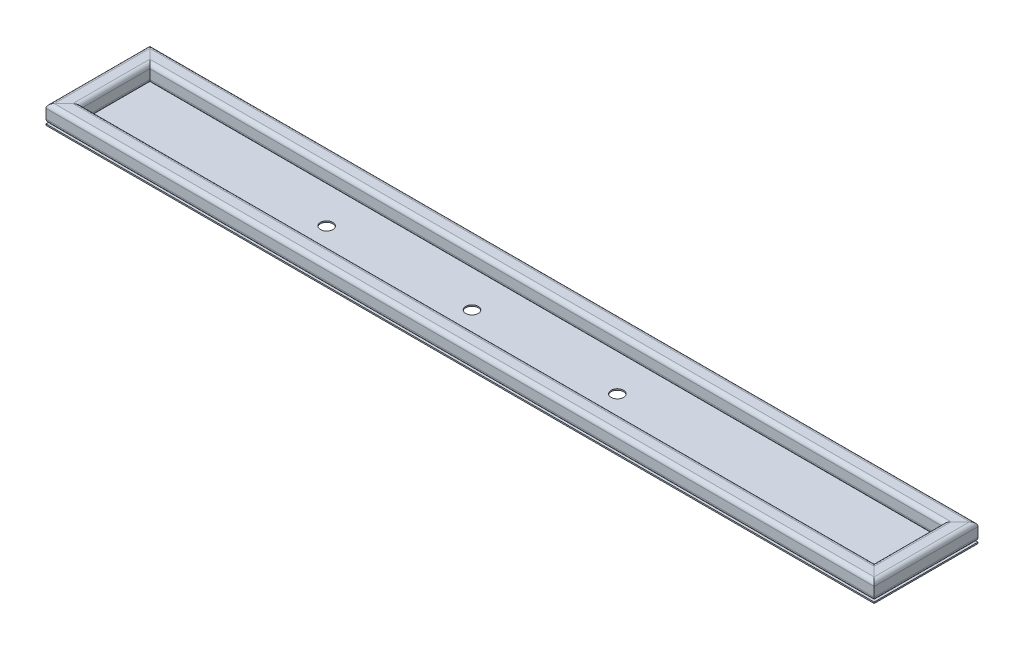
SolidWorks part; units mm, degrees
ref_plane "Alzado" through (0, 0, 0) normal (0, 0, 1) x (1, 0, 0)
ref_plane "Planta" through (0, 0, 0) normal (0, 1, 0) x (1, 0, 0)
ref_plane "Vista lateral" through (0, 0, 0) normal (1, 0, 0) x (0, 0, -1)
sketch "Croquis1" plane through (0, 0, 0) normal (0, 1, 0) x (1, 0, 0)
  line L1 (-598.2, 75) -> (598.2, 75)
  line L2 (-598.2, 75) -> (-598.2, -75)
  line L3 (-598.2, -75) -> (598.2, -75)
  line L4 (598.2, 75) -> (598.2, -75)
  line L5 (-598.2, 75) -> (598.2, -75) construction
  line L6 (-598.2, -75) -> (598.2, 75) construction
  point P0 (0, 0)
  dimension "D1" = 150
  dimension "D2" = 1196.4
other "Tubo cuadrado 2 X 2 X 0.25(1)"
ref_plane "Plano1" through (-585.5, 12.7, -75) normal (0, 0, 1) x (1, 0, 0)
sketch "Sketch1" plane through (-585.5, 12.7, -75) normal (0, 0, 1) x (1, 0, 0)
  line L0 (-6.7, -9.7) -> (6.7, -9.7)
  line L1 (-9.7, -6.7) -> (-9.7, 6.7)
  line L2 (6.7, 9.7) -> (-6.7, 9.7)
  line L3 (9.7, 6.7) -> (9.7, -6.7)
  line L4 (-6.7, -12.7) -> (6.7, -12.7)
  line L5 (-12.7, -6.7) -> (-12.7, 6.7)
  line L6 (6.7, 12.7) -> (-6.7, 12.7)
  line L7 (12.7, 6.7) -> (12.7, -6.7)
  line L8 (0, 0) -> (9.7, 0) construction
  line L9 (0, 0) -> (0, 9.7) construction
  arc A0 (12.7, 6.7) -> (6.7, 12.7) centre (6.7, 6.7) ccw
  arc A1 (6.7, -12.7) -> (12.7, -6.7) centre (6.7, -6.7) ccw
  arc A2 (-12.7, -6.7) -> (-6.7, -12.7) centre (-6.7, -6.7) ccw
  arc A3 (-6.7, 12.7) -> (-12.7, 6.7) centre (-6.7, 6.7) ccw
  arc A4 (-6.7, 9.7) -> (-9.7, 6.7) centre (-6.7, 6.7) ccw
  arc A5 (9.7, 6.7) -> (6.7, 9.7) centre (6.7, 6.7) ccw
  arc A6 (6.7, -9.7) -> (9.7, -6.7) centre (6.7, -6.7) ccw
  arc A7 (-9.7, -6.7) -> (-6.7, -9.7) centre (-6.7, -6.7) ccw
  point P3 (0, 12.7)
  point P4 (12.7, 0)
  point P5 (0, -12.7)
  point P6 (-12.7, 0)
  point P7 (-12.7, 12.7)
  point P8 (-12.7, -12.7)
  point P33 (0, 0)
  point P35 (12.7, -12.7)
  point P36 (12.7, 12.7)
  point P37 (0, 0)
  dimension "D1" = 6
  dimension "Thickness" = 3
  dimension "V_leg" = 25.4
sketch "Croquis3" plane through (0, 0, 0) normal (0, -1, 0) x (1, 0, 0)
  line L1 (598.2, 75) -> (-598.2, 75)
  line L2 (598.2, 75) -> (598.2, -75)
  line L3 (598.2, -75) -> (-598.2, -75)
  line L4 (-598.2, 75) -> (-598.2, -75)
  line L5 (598.2, 75) -> (-598.2, -75) construction
  line L6 (598.2, -75) -> (-598.2, 75) construction
  point P0 (0, 0)
extrude "Saliente-Extruir1" add sketch "Croquis3" along normal blind 1.9 separate body
ref_plane "Plano2" through (0, 0, 0) normal (0, 0, 1) x (1, 0, 0)
sketch "Croquis4" plane through (0, 0, 0) normal (0, 1, 0) x (1, 0, 0)
  circle A0 centre (-268.2099, 0) radius 7.9375
  circle A3 centre (-58.2099, 0) radius 7.9375
  circle A6 centre (151.7851, 0) radius 7.9375
sketch "Croquis6" plane through (0, -1.9, 0) normal (0, -1, 0) x (1, 0, 0)
  line L0 (-598.2, 75) -> (-598.2, -75) construction
  line L1 (-598.2, -75) -> (-598.2, 0) construction
  line L2 (-598.2, 0) -> (-267.8, 0) construction
  line L3 (7.37, 0) -> (-7.37, 0) construction
  line L4 (-267.8, 0) -> (-57.8, 0) construction
  line L5 (-57.8, 0) -> (152.2, 0) construction
  line L6 (598.2, -75) -> (598.2, 75) construction
  circle A0 centre (-267.8, 0) radius 9
  circle A1 centre (-57.8, 0) radius 9
  circle A2 centre (152.2, 0) radius 9
  dimension "D4" = 18
  dimension "D5" = 18
  dimension "D6" = 18
  dimension "D1" = 446
  dimension "D2" = 210
  dimension "D3" = 210
extrude "Cortar-Extruir1" cut sketch "Croquis6" against normal blind 10
